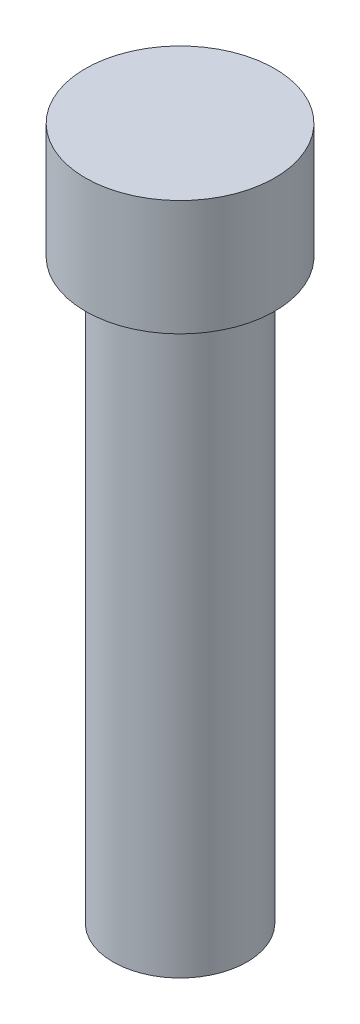
SolidWorks part; units mm, degrees
ref_plane "前视基准面" through (0, 0, 0) normal (0, 0, 1) x (1, 0, 0)
ref_plane "上视基准面" through (0, 0, 0) normal (0, 1, 0) x (1, 0, 0)
ref_plane "右视基准面" through (0, 0, 0) normal (1, 0, 0) x (0, 0, -1)
other "Configuration Table"
sketch "草图1" plane through (0, 0, 0) normal (0, 1, 0) x (1, 0, 0)
  circle A0 centre (0, 0) radius 2.9
  dimension "D1" = 5.8
extrude "凸台-拉伸1" add sketch "草图1" along normal blind 25 contours A0
sketch "草图2" plane through (0, 25, 0) normal (0, 1, 0) x (1, 0, 0)
  circle A0 centre (0, 0) radius 4.1
  dimension "D1" = 8.2
extrude "凸台-拉伸2" add sketch "草图2" along normal blind 5
